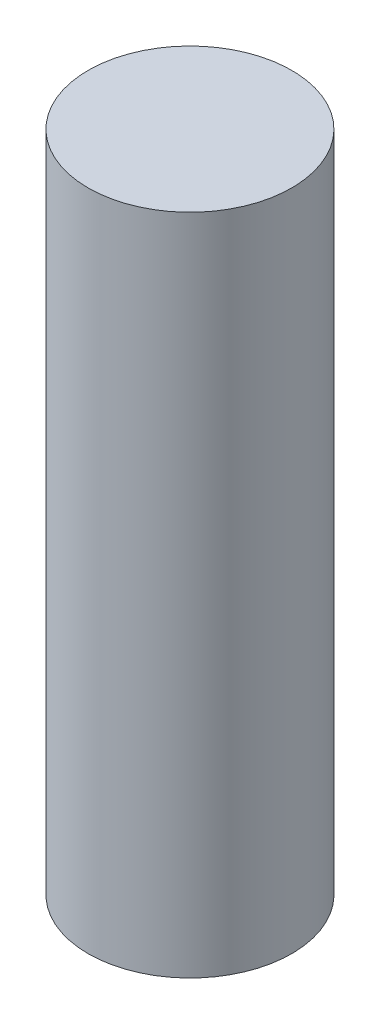
SolidWorks part; units mm, degrees
ref_plane "Front Plane" through (0, 0, 0) normal (0, 0, 1) x (1, 0, 0)
ref_plane "Top Plane" through (0, 0, 0) normal (0, 1, 0) x (1, 0, 0)
ref_plane "Right Plane" through (0, 0, 0) normal (1, 0, 0) x (0, 0, -1)
sketch "Sketch1" plane through (0, 0, 0) normal (0, 1, 0) x (1, 0, 0)
  circle A0 centre (0, 0) radius 4
  dimension "D1" = 8
extrude "Boss-Extrude1" add sketch "Sketch1" along normal blind 26.05
